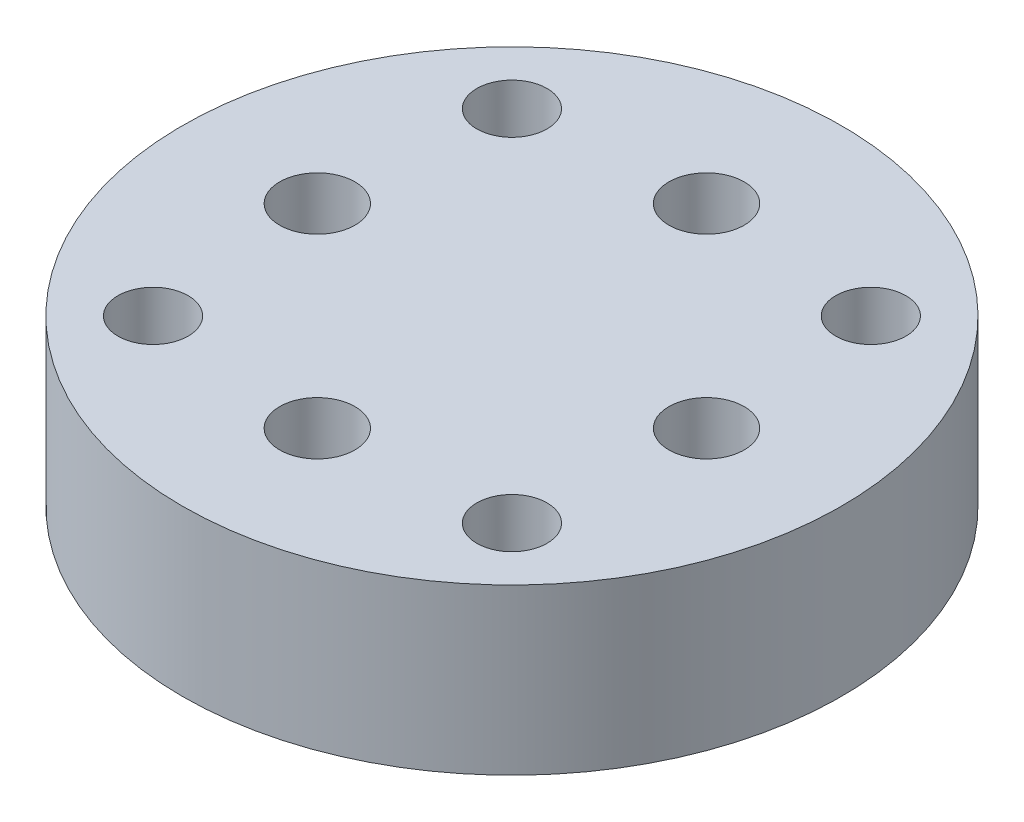
SolidWorks part; units mm, degrees
material "6061 Alloy"
ref_plane "Front Plane" through (0, 0, 0) normal (0, 0, 1) x (1, 0, 0)
ref_plane "Top Plane" through (0, 0, 0) normal (0, 1, 0) x (1, 0, 0)
ref_plane "Right Plane" through (0, 0, 0) normal (1, 0, 0) x (0, 0, -1)
sketch "Sketch2" plane through (0, 0, 0) normal (0, 1, 0) x (1, 0, 0)
  circle A0 centre (0, 0) radius 12.7
  dimension "D1" = 25.4
extrude "Boss-Extrude1" add sketch "Sketch2" along normal blind 6.35
hole_wizard "CSK for M2.5 Flat Head Machine Screw1" positions "Sketch4" profile "Sketch3" countersink size "M2.5" standard "ANSI Metric" end condition through all
sketch "Sketch4" plane through (0, 0, 0) normal (0, -1, 0) x (-1, 0, 0)
  line L0 (7.5, 0) -> (-7.5, 0) construction
  line L3 (0, -7.5) -> (0, 7.5) construction
  point P0 (7.5, 0)
  point P2 (-7.5, 0)
  point P4 (0, -7.5)
  point P6 (0, 7.5)
  dimension "D1" = 15
sketch "Sketch3" plane through (-7.5, 0, 0) normal (1, 0, 0) x (0, 0, -1)
  line L0 (0, 0) -> (0, 6.35)
  line L1 (0, 6.35) -> (1.45, 6.35)
  line L2 (1.45, 6.35) -> (1.45, 1.3)
  line L3 (1.45, 1.3) -> (2.75, 0)
  line L5 (2.75, 0) -> (0, 0)
  line L6 (-1.45, 1.3) -> (-2.75, 0) construction
  line L11 (0, -6.35) -> (0, 107.95) construction
  dimension "Thru Hole Dia." = 2.9
  dimension "Thru Hole Depth" = 6.35
  dimension "Near C'Sink Dia." = 5.5
  dimension "Near C'Sink Angle" = 90
hole_wizard "#6-32 Tapped Hole1" positions "Sketch6" profile "Sketch5" tap size "#6-32" standard "ANSI Inch"
sketch "Sketch6" plane through (0, 0, 0) normal (0, -1, 0) x (-1, 0, 0)
  line L0 (6.9148, -6.9148) -> (-6.9148, 6.9148) construction
  line L3 (-6.9148, -6.9148) -> (6.9148, 6.9148) construction
  point P0 (6.9148, -6.9148)
  point P2 (-6.9148, -6.9148)
  point P4 (-6.9148, 6.9148)
  point P6 (6.9148, 6.9148)
  dimension "D1" = 19.558
sketch "Sketch5" plane through (-6.9148, 0, 6.9148) normal (1, 0, 0) x (0, 0, -1)
  line L0 (0, 0) -> (0, 10.2005)
  line L1 (0, 10.2005) -> (1.3525, 9.3878)
  line L2 (1.3525, 9.3878) -> (1.3525, 0)
  line L5 (1.3525, 0) -> (0, 0)
  line L10 (0, 10.2005) -> (-1.3526, 9.3878) construction
  line L11 (0, -6.35) -> (0, 107.95) construction
  dimension "Tap Drill Dia." = 2.7051
  dimension "Tap Drill Depth" = 9.3878
  dimension "Drill Angle" = 118
